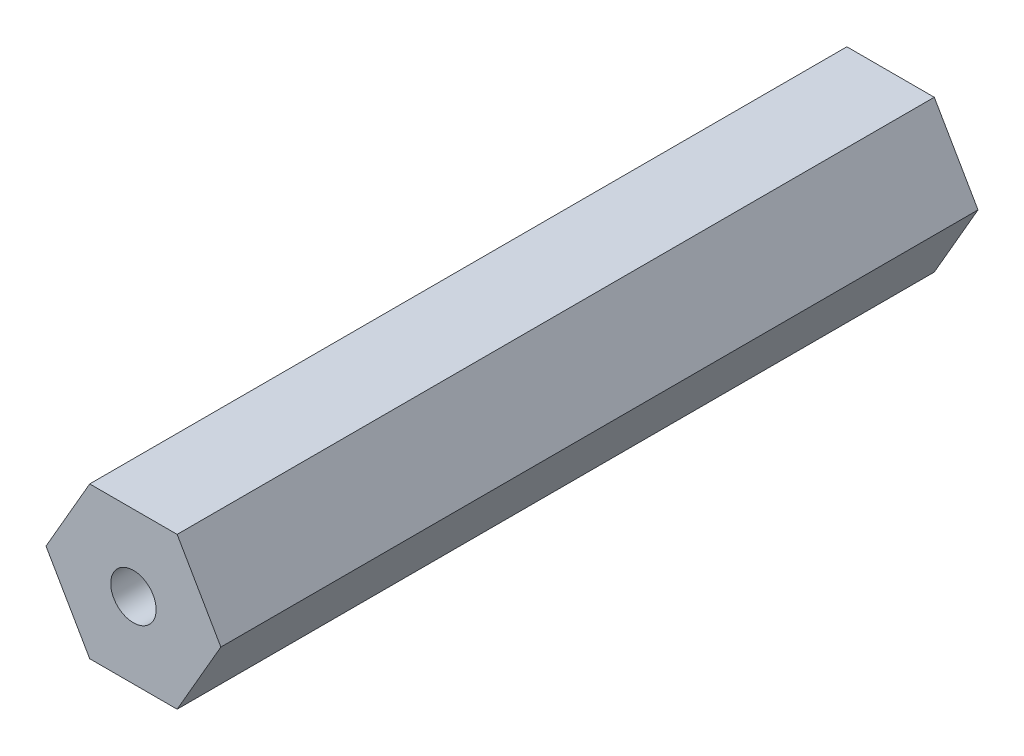
SolidWorks part; units mm, degrees
ref_plane "Front Plane" through (0, 0, 0) normal (0, 0, 1) x (1, 0, 0)
ref_plane "Top Plane" through (0, 0, 0) normal (0, 1, 0) x (1, 0, 0)
ref_plane "Right Plane" through (0, 0, 0) normal (1, 0, 0) x (0, 0, -1)
sketch "Sketch1" plane through (0, 0, 0) normal (0, 0, 1) x (1, 0, 0)
  line L1 (5.7735, 0) -> (2.8868, 5)
  line L2 (2.8868, 5) -> (-2.8868, 5)
  line L3 (-2.8868, 5) -> (-5.7735, 0)
  line L4 (-5.7735, 0) -> (-2.8868, -5)
  line L5 (-2.8868, -5) -> (2.8868, -5)
  line L6 (2.8868, -5) -> (5.7735, 0)
  circle A0 centre (0, 0) radius 5 construction
  circle A1 centre (0, 0) radius 1.5
extrude "Boss-Extrude1" add sketch "Sketch1" along normal blind 50
